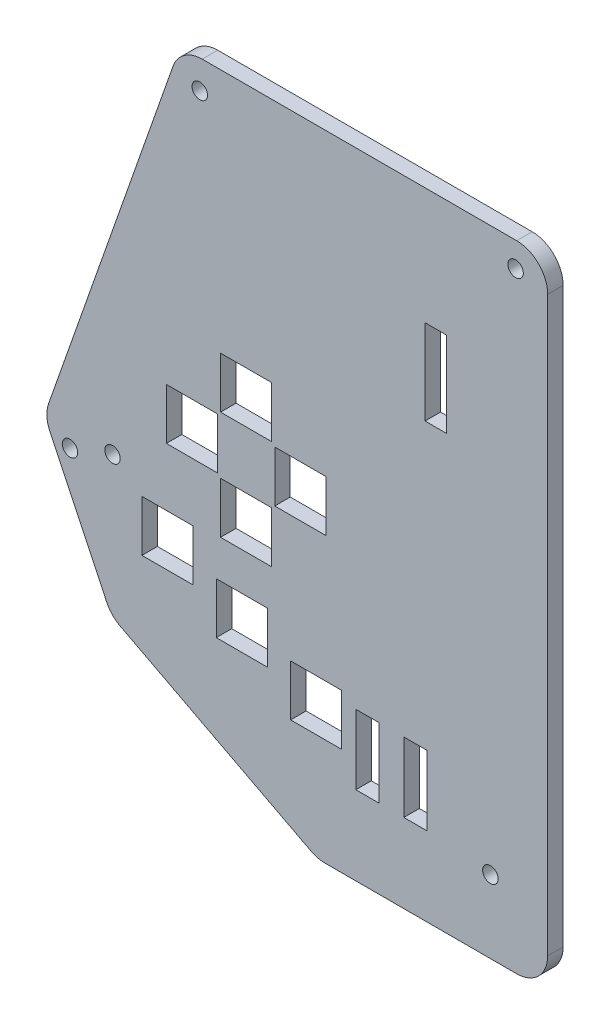
SolidWorks part; units mm, degrees
ref_plane "Front Plane" through (0, 0, 0) normal (0, 0, 1) x (1, 0, 0)
ref_plane "Top Plane" through (0, 0, 0) normal (0, 1, 0) x (1, 0, 0)
ref_plane "Right Plane" through (0, 0, 0) normal (1, 0, 0) x (0, 0, -1)
sketch "Sketch1" plane through (0, 0, 0) normal (0, 0, 1) x (1, 0, 0)
  line L6 (-20.066, -57.15) -> (46.99, -57.15) construction
  line L7 (-12.446, -73.152) -> (46.99, -73.152) construction
  line L8 (-3.3141, 6.35) -> (48.26, 6.35)
  line L9 (53.34, 1.27) -> (53.34, -92.71)
  line L10 (48.26, -97.79) -> (16.847, -97.79)
  line L16 (-8.1072, 2.9529) -> (-28.5162, -55.1739)
  line L18 (-20.066, -57.15) -> (-29.21, -57.15) construction
  line L26 (0, 0) -> (46.99, 0) construction
  line L27 (46.99, 0) -> (46.99, -88.9) construction
  line L28 (46.99, -88.9) -> (17.78, -88.9) construction
  line L29 (17.78, -88.9) -> (-12.446, -73.152) construction
  line L30 (-12.446, -73.152) -> (-20.066, -57.15) construction
  line L31 (-20.066, -57.15) -> (0, 0) construction
  line L32 (46.99, -57.15) -> (46.99, -88.9) construction
  line L33 (17.78, -88.9) -> (15.603, -97.79) construction
  line L34 (-12.446, -73.152) -> (-17.9301, -78.4424) construction
  line L35 (14.4997, -97.2152) -> (-16.7505, -80.9336)
  line L36 (-28.3096, -59.0409) -> (-18.9898, -78.6124)
  arc A0 (53.34, -92.71) -> (48.26, -97.79) centre (48.26, -92.71) cw
  arc A1 (14.4997, -97.2152) -> (16.847, -97.79) centre (16.847, -92.71) ccw
  arc A2 (-16.7505, -80.9336) -> (-18.9898, -78.6124) centre (-14.4033, -76.4284) cw
  arc A3 (-28.5162, -55.1739) -> (-28.3096, -59.0409) centre (-23.723, -56.8568) ccw
  arc A4 (-8.1072, 2.9529) -> (-3.3141, 6.35) centre (-3.3141, 1.27) cw
  arc A5 (48.26, 6.35) -> (53.34, 1.27) centre (48.26, 1.27) cw
  point P13 (53.34, -97.79)
  point P32 (53.34, 6.35)
  dimension "D8" = 5.08
  dimension "D1" = 88.9
  dimension "D2" = 29.21
  dimension "D3" = 59.436
  dimension "D4" = 67.056
  dimension "D5" = 104.14
  dimension "D6" = 82.55
  dimension "D7" = 46.99
  dimension "D13" = 103.76
  dimension "D17" = 108.51
sketch "Sketch3" plane through (0, 0, 0) normal (0, 0, 1) x (1, 0, 0)
  line L6 (-20.066, -57.15) -> (46.99, -57.15) construction
  line L7 (-12.446, -73.152) -> (46.99, -73.152) construction
  line L8 (0, 0) -> (46.99, 0) construction
  line L9 (46.99, 0) -> (46.99, -88.9) construction
  line L10 (46.99, -88.9) -> (17.78, -88.9) construction
  line L11 (17.78, -88.9) -> (-12.446, -73.152) construction
  line L12 (-12.446, -73.152) -> (-20.066, -57.15) construction
  line L13 (-20.066, -57.15) -> (0, 0) construction
  line L14 (3.8784, -55.88) -> (3.8784, -38.1) construction
  circle A0 centre (3.8784, -38.1) radius 5.08
  circle A1 centre (-5.0116, -46.99) radius 5.08
  circle A2 centre (3.8784, -55.88) radius 5.08
  circle A3 centre (12.7684, -46.99) radius 5.08
  circle A4 centre (-9.144, -65.024) radius 5.08
  circle A5 centre (3.048, -70.612) radius 5.08
  circle A6 centre (15.24, -76.2) radius 5.08
  dimension "D7" = 10.16
  dimension "D1" = 43.1116
  dimension "D2" = 8.89
  dimension "D3" = 8.89
  dimension "D4" = 46.99
  dimension "D5" = 8.89
  dimension "D6" = 8.89
  dimension "D8" = 12.192
  dimension "D9" = 5.588
  dimension "D10" = 5.588
  dimension "D11" = 12.192
  dimension "D12" = 43.942
  dimension "D13" = 70.612
sketch "Sketch10" plane through (0, 0, 0) normal (0, 0, 1) x (1, 0, 0)
  line L1 (53.34, 1.27) -> (53.34, -92.71)
  line L6 (48.26, -97.79) -> (16.847, -97.79)
  line L16 (-8.1072, 2.9529) -> (-28.5162, -55.1739)
  line L19 (53.34, 1.27) -> (53.34, -92.71) construction
  line L21 (-8.1072, 2.9529) -> (-28.5162, -55.1739) construction
  line L24 (14.4997, -97.2152) -> (-16.7505, -80.9336)
  line L25 (-18.9898, -78.6124) -> (-28.3096, -59.0409)
  line L26 (-3.3141, 6.35) -> (48.26, 6.35)
  arc A0 (-18.9898, -78.6124) -> (-16.7505, -80.9336) centre (-14.4033, -76.4284) ccw
  arc A1 (16.847, -97.79) -> (14.4997, -97.2152) centre (16.847, -92.71) cw
  arc A2 (-28.5162, -55.1739) -> (-28.3096, -59.0409) centre (-23.723, -56.8568) ccw
  arc A3 (53.34, -92.71) -> (48.26, -97.79) centre (48.26, -92.71) cw
  arc A4 (-8.1072, 2.9529) -> (-3.3141, 6.35) centre (-3.3141, 1.27) cw
  arc A5 (48.26, 6.35) -> (53.34, 1.27) centre (48.26, 1.27) cw
  point P13 (15.603, -97.79)
  point P17 (-29.21, -57.15)
  point P20 (53.34, -97.79)
  dimension "D1" = 5.08
extrude "Boss-Extrude1" add sketch "Sketch10" along normal blind 2.54
sketch "Sketch11" plane through (0, 0, 2.54) normal (0, 0, 1) x (1, 0, 0)
  line L0 (46.99, -88.9) -> (17.78, -88.9) construction
  line L5 (33.561, -73.406) -> (29.751, -73.406)
  line L6 (33.561, -73.406) -> (33.561, -84.836)
  line L11 (33.561, -84.836) -> (29.751, -84.836)
  line L12 (29.751, -73.406) -> (29.751, -84.836)
  line L18 (46.99, 0) -> (46.99, -88.9) construction
  line L23 (25.687, -73.406) -> (21.877, -73.406)
  line L24 (25.687, -73.406) -> (25.687, -84.836)
  line L29 (25.687, -84.836) -> (21.877, -84.836)
  line L30 (21.877, -73.406) -> (21.877, -84.836)
  line L42 (8.0694, -51.689) -> (-0.3126, -51.689)
  line L43 (8.0694, -51.689) -> (8.0694, -60.071)
  line L44 (8.0694, -60.071) -> (-0.3126, -60.071)
  line L45 (-0.3126, -51.689) -> (-0.3126, -60.071)
  line L46 (-0.8206, -42.799) -> (-9.2026, -42.799)
  line L47 (-0.8206, -42.799) -> (-0.8206, -51.181)
  line L48 (-0.8206, -51.181) -> (-9.2026, -51.181)
  line L49 (-9.2026, -42.799) -> (-9.2026, -51.181)
  line L52 (8.0694, -42.291) -> (-0.3126, -42.291)
  line L53 (-0.3126, -33.909) -> (-0.3126, -42.291)
  line L54 (16.9594, -42.799) -> (8.5774, -42.799)
  line L55 (16.9594, -42.799) -> (16.9594, -51.181)
  line L56 (16.9594, -51.181) -> (8.5774, -51.181)
  line L57 (8.5774, -42.799) -> (8.5774, -51.181)
  line L58 (-0.3126, -33.909) -> (8.0694, -33.909)
  line L59 (8.0694, -33.909) -> (8.0694, -42.291)
  line L60 (3.8784, -51.689) -> (3.8784, -60.071) construction
  line L61 (-0.3126, -55.88) -> (8.0694, -55.88) construction
  line L62 (-5.0116, -51.181) -> (-5.0116, -42.799) construction
  line L63 (-9.2026, -46.99) -> (-0.8206, -46.99) construction
  line L64 (12.7684, -42.799) -> (12.7684, -51.181) construction
  line L65 (8.5774, -46.99) -> (16.9594, -46.99) construction
  line L66 (3.8784, -33.909) -> (3.8784, -42.291) construction
  line L67 (-0.3126, -38.1) -> (8.0694, -38.1) construction
  line L68 (-4.826, -60.706) -> (-4.826, -69.088)
  line L69 (-13.208, -65.024) -> (-5.08, -65.024) construction
  line L70 (-9.144, -60.96) -> (-9.144, -69.088) construction
  line L71 (-4.826, -69.088) -> (-13.208, -69.088)
  line L72 (-13.208, -60.706) -> (-13.208, -69.088)
  line L73 (-4.826, -60.706) -> (-13.208, -60.706)
  line L74 (7.366, -66.294) -> (7.366, -74.676)
  line L75 (-1.016, -70.612) -> (7.112, -70.612) construction
  line L76 (3.048, -66.548) -> (3.048, -74.676) construction
  line L77 (7.366, -74.676) -> (-1.016, -74.676)
  line L78 (-1.016, -66.294) -> (-1.016, -74.676)
  line L79 (7.366, -66.294) -> (-1.016, -66.294)
  line L80 (19.558, -71.882) -> (19.558, -80.264)
  line L81 (11.176, -76.2) -> (19.304, -76.2) construction
  line L82 (15.24, -72.136) -> (15.24, -80.264) construction
  line L83 (19.558, -80.264) -> (11.176, -80.264)
  line L84 (11.176, -71.882) -> (11.176, -80.264)
  line L85 (19.558, -71.882) -> (11.176, -71.882)
  dimension "D1" = 4.064
  dimension "D3" = 13.429
  dimension "D4" = 11.43
  dimension "D5" = 3.81
  dimension "D6" = 4.064
  dimension "D7" = 11.43
  dimension "D8" = 4.064
  dimension "D13" = 3.81
  dimension "D21" = 8.382
  dimension "D22" = 8.382
extrude "Cut-Extrude1" cut sketch "Sketch11" against normal through all both and the other way through all
sketch "Sketch12" plane through (0, 0, 0) normal (0, 0, -1) x (-1, 0, 0)
  line L0 (20.066, -57.15) -> (-46.99, -57.15) construction
  line L1 (-37.465, -31.4407) -> (-43.942, -85.852) construction
  line L2 (-46.99, 0) -> (-46.99, -88.9) construction
  line L5 (18.034, -57.15) -> (20.066, -57.15) construction
  line L10 (-46.99, -88.9) -> (-17.78, -88.9) construction
  circle A2 centre (18.034, -57.15) radius 1.27
  circle A3 centre (-43.942, -85.852) radius 1.27
  dimension "D1" = 2.54
  dimension "D6" = 2.032
  dimension "D3" = 54.7954
  dimension "D11" = 3.048
  dimension "D12" = 3.048
extrude "Cut-Extrude2" cut sketch "Sketch12" against normal through all both and the other way through all
sketch "Sketch13" plane through (0, 0, 0) normal (0, 0, -1) x (-1, 0, 0)
  line L0 (28.3096, -59.0409) -> (18.9898, -78.6124) construction
  line L1 (8.1072, 2.9529) -> (28.5162, -55.1739) construction
  line L2 (3.3141, 6.35) -> (-48.26, 6.35) construction
  line L4 (-53.34, 1.27) -> (-53.34, -92.71) construction
  circle A1 centre (25.0123, -59.762) radius 1.27
  circle A4 centre (-48.0822, 2.286) radius 1.27
  circle A5 centre (3.7187, 1.651) radius 1.27
  dimension "D1" = 2.54
  dimension "D2" = 4.826
  dimension "D4" = 4.064
  dimension "D3" = 2.667
  dimension "D5" = 5.2578
  dimension "D6" = 4.699
  dimension "D7" = 4.572
extrude "Cut-Extrude3" cut sketch "Sketch13" against normal through all both and the other way through all
sketch "Sketch14" plane through (0, 0, 0) normal (0, 0, -1) x (-1, 0, 0)
  line L0 (-36.7885, -26.7831) -> (-33.2325, -26.7831)
  line L1 (-36.7885, -12.8131) -> (-36.7885, -26.7831)
  line L2 (-33.2325, -12.8131) -> (-36.7885, -12.8131)
  line L3 (-33.2325, -12.8131) -> (-33.2325, -26.7831)
  line L4 (-53.34, 1.27) -> (-53.34, -92.71) construction
  line L5 (3.3141, 6.35) -> (-48.26, 6.35) construction
  dimension "D1" = 16.5515
  dimension "D2" = 13.97
  dimension "D3" = 19.1631
extrude "Cut-Extrude4" cut sketch "Sketch14" against normal through all both and the other way through all
